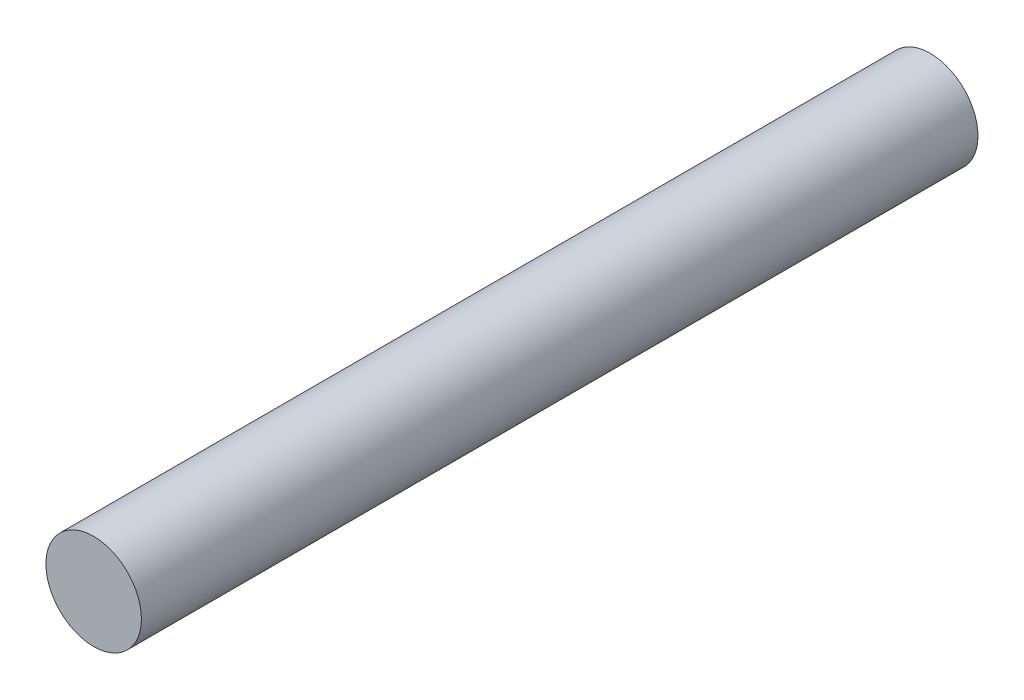
SolidWorks part; units mm, degrees
ref_plane "Front Plane" through (0, 0, 0) normal (0, 0, 1) x (1, 0, 0)
ref_plane "Top Plane" through (0, 0, 0) normal (0, 1, 0) x (1, 0, 0)
ref_plane "Right Plane" through (0, 0, 0) normal (1, 0, 0) x (0, 0, -1)
sketch "Sketch1" plane through (0, 0, 0) normal (0, 0, 1) x (1, 0, 0)
  circle A0 centre (0, 0) radius 2.5
  dimension "D1" = 5
extrude "Boss-Extrude1" add sketch "Sketch1" along normal blind 43.8
